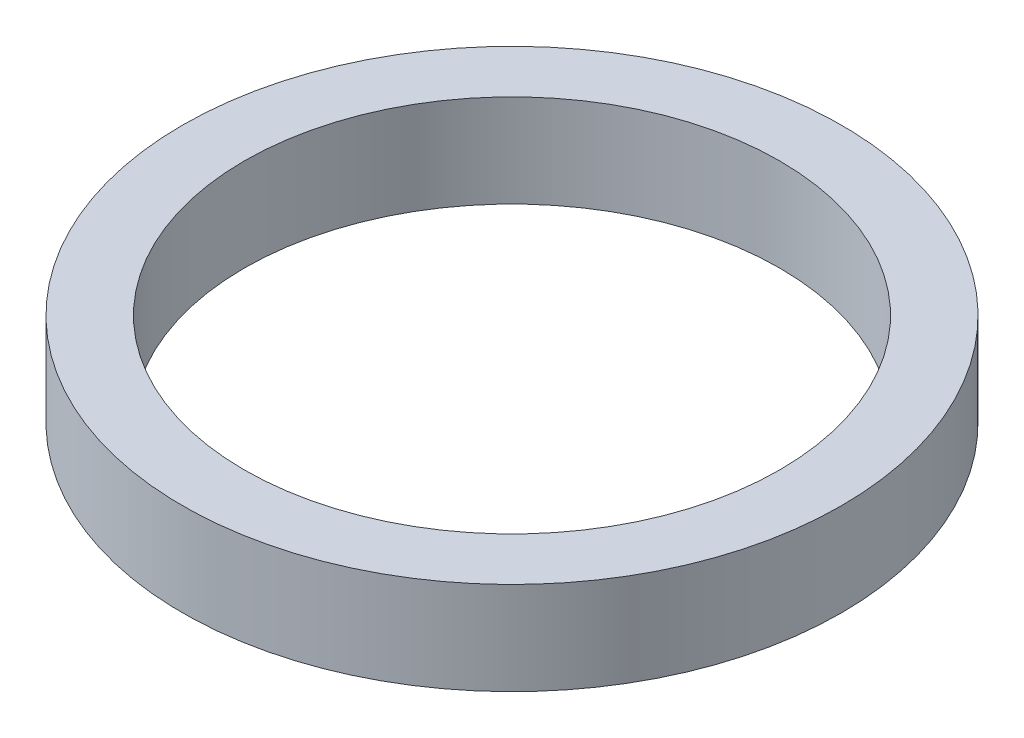
SolidWorks part; units mm, degrees
ref_plane "Płaszczyzna przednia" through (0, 0, 0) normal (0, 0, 1) x (1, 0, 0)
ref_plane "Płaszczyzna górna" through (0, 0, 0) normal (0, 1, 0) x (1, 0, 0)
ref_plane "Płaszczyzna prawa" through (0, 0, 0) normal (1, 0, 0) x (0, 0, -1)
sketch "Szkic1" plane through (0, 0, 0) normal (0, 0, 1) x (1, 0, 0)
  line L0 (0, 10) -> (0, 0) construction
  line L1 (-86.5, 30) -> (-86.5, 0)
  line L2 (-106.5, 30) -> (-106.5, 0)
  line L3 (-106.5, 30) -> (-86.5, 30)
  line L4 (-106.5, 0) -> (-86.5, 0)
  dimension "D1" = 86.5
  dimension "D2" = 106.5
  dimension "D3" = 30
revolve "Obrót1" add sketch "Szkic1" angle 360 about L0
